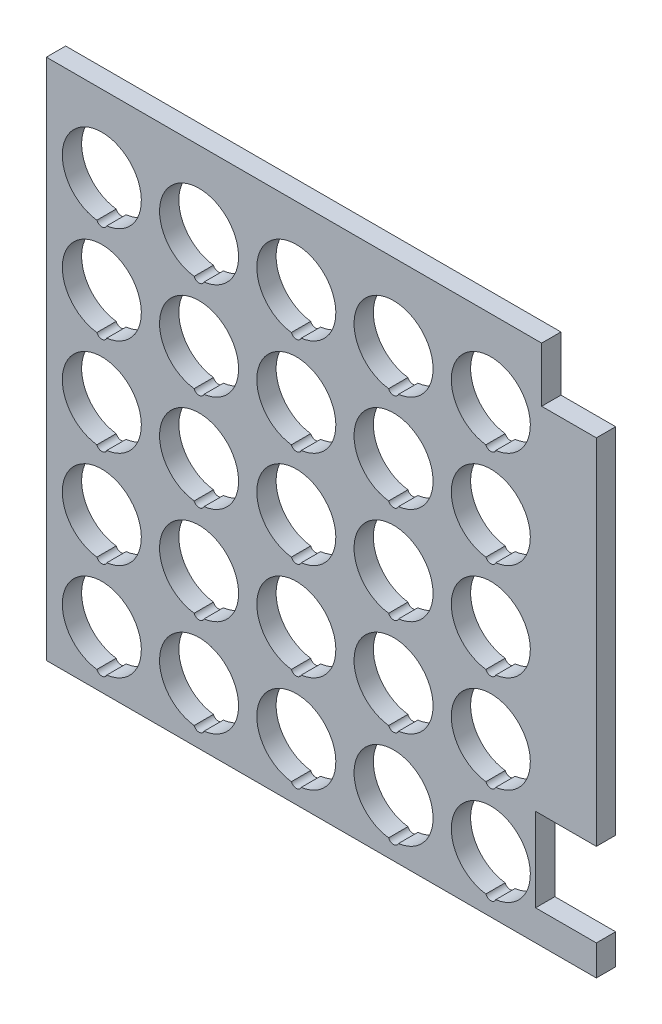
SolidWorks part; units mm, degrees
ref_plane "Front Plane" through (0, 0, 0) normal (0, 0, 1) x (1, 0, 0)
ref_plane "Top Plane" through (0, 0, 0) normal (0, 1, 0) x (1, 0, 0)
ref_plane "Right Plane" through (0, 0, 0) normal (1, 0, 0) x (0, 0, -1)
sketch "Sketch2" plane through (0, 0, 0) normal (0, 0, 1) x (1, 0, 0)
  line L1 (0, 0) -> (180.975, 0)
  line L2 (0, 0) -> (0, 161.925)
  line L3 (0, 161.925) -> (180.975, 161.925)
  line L4 (180.975, 0) -> (180.975, 161.925)
  dimension "D1" = 180.975
  dimension "D2" = 161.925
extrude "Boss-Extrude1" add sketch "Sketch2" along normal blind 6.35
sketch "Sketch6" plane through (0, 0, 6.35) normal (0, 0, 1) x (1, 0, 0)
  line L1 (0, 0) -> (180.975, 0)
  line L2 (0, 0) -> (0, -10)
  line L3 (0, -10) -> (180.975, -10)
  line L4 (180.975, 0) -> (180.975, -10)
  dimension "D1" = 10
extrude "Boss-Extrude2" add sketch "Sketch6" against normal up to surface (6.35 mm away) up to face at (90.4875, 80.9625, 0)
sketch "Sketch3" plane through (0, 0, 6.35) normal (0, 0, 1) x (1, 0, 0)
  line L2 (0, 161.925) -> (0, -10) construction
  line L3 (180.975, 161.925) -> (0, 161.925) construction
  circle A0 centre (18.25, 8.675) radius 13
  circle A1 centre (50.25, 8.675) radius 13
  circle A2 centre (82.25, 8.675) radius 13
  circle A3 centre (114.25, 8.675) radius 13
  circle A4 centre (146.25, 8.675) radius 13
  circle A5 centre (50.25, 40.675) radius 13
  circle A6 centre (82.25, 40.675) radius 13
  circle A7 centre (114.25, 40.675) radius 13
  circle A8 centre (146.25, 40.675) radius 13
  circle A9 centre (50.25, 72.675) radius 13
  circle A10 centre (82.25, 72.675) radius 13
  circle A11 centre (114.25, 72.675) radius 13
  circle A12 centre (146.25, 72.675) radius 13
  circle A13 centre (50.25, 104.675) radius 13
  circle A14 centre (82.25, 104.675) radius 13
  circle A15 centre (114.25, 104.675) radius 13
  circle A16 centre (146.25, 104.675) radius 13
  circle A17 centre (50.25, 136.675) radius 13
  circle A18 centre (82.25, 136.675) radius 13
  circle A19 centre (114.25, 136.675) radius 13
  circle A20 centre (146.25, 136.675) radius 13
  circle A21 centre (18.25, 40.675) radius 13
  circle A22 centre (18.25, 72.675) radius 13
  circle A23 centre (18.25, 104.675) radius 13
  circle A24 centre (18.25, 136.675) radius 13
  dimension "D2" = 25.25
  dimension "D3" = 26
  dimension "D1" = 18.25
  dimension "D4" = 5
  dimension "D5" = 5
extrude "Cut-Extrude1" cut sketch "Sketch3" against normal through all
sketch "Sketch4" plane through (0, 0, 6.35) normal (0, 0, 1) x (1, 0, 0)
  line L0 (18.25, 21.675) -> (18.25, -4.325) construction
  circle A0 centre (18.25, 8.675) radius 13 construction
  circle A1 centre (18.25, -3.575) radius 1.75
  circle A2 centre (50.25, -3.575) radius 1.75
  circle A3 centre (82.25, -3.575) radius 1.75
  circle A4 centre (114.25, -3.575) radius 1.75
  circle A5 centre (146.25, -3.575) radius 1.75
  circle A6 centre (50.25, 28.425) radius 1.75
  circle A7 centre (82.25, 28.425) radius 1.75
  circle A8 centre (114.25, 28.425) radius 1.75
  circle A9 centre (146.25, 28.425) radius 1.75
  circle A10 centre (50.25, 60.425) radius 1.75
  circle A11 centre (82.25, 60.425) radius 1.75
  circle A12 centre (114.25, 60.425) radius 1.75
  circle A13 centre (146.25, 60.425) radius 1.75
  circle A14 centre (50.25, 92.425) radius 1.75
  circle A15 centre (82.25, 92.425) radius 1.75
  circle A16 centre (114.25, 92.425) radius 1.75
  circle A17 centre (146.25, 92.425) radius 1.75
  circle A18 centre (50.25, 124.425) radius 1.75
  circle A19 centre (82.25, 124.425) radius 1.75
  circle A20 centre (114.25, 124.425) radius 1.75
  circle A21 centre (146.25, 124.425) radius 1.75
  circle A22 centre (18.25, 28.425) radius 1.75
  circle A23 centre (18.25, 60.425) radius 1.75
  circle A24 centre (18.25, 92.425) radius 1.75
  circle A25 centre (18.25, 124.425) radius 1.75
  dimension "D2" = 3.5
  dimension "D1" = 0.75
  dimension "D3" = 5
  dimension "D4" = 5
extrude "Cut-Extrude9" cut sketch "Sketch4" against normal through all
sketch "Sketch5" plane through (0, 0, 6.35) normal (0, 0, 1) x (1, 0, 0)
  line L0 (13, 140.675) -> (15.5, 140.675) construction
  circle A0 centre (13, 140.675) radius 1
  circle A1 centre (15.5, 140.675) radius 1
  point P4 (18.25, 136.675)
  point P5 (14.25, 140.675)
  dimension "D1" = 2
  dimension "D2" = 2
  dimension "D3" = 2.5
  dimension "D4" = 4
  dimension "D5" = 4
sketch "Sketch7" plane through (0, 0, 6.35) normal (0, 0, 1) x (1, 0, 0)
  line L0 (180.975, -10) -> (180.975, 161.925) construction
  line L1 (180.975, 0) -> (160.975, 0)
  line L2 (180.975, 0) -> (180.975, 27.5)
  line L3 (180.975, 27.5) -> (160.975, 27.5)
  line L4 (160.975, 0) -> (160.975, 27.5)
  line L5 (0, -10) -> (180.975, -10) construction
  line L6 (180.975, 161.925) -> (162.975, 161.925)
  line L7 (180.975, 161.925) -> (180.975, 143.925)
  line L8 (180.975, 143.925) -> (162.975, 143.925)
  line L9 (162.975, 161.925) -> (162.975, 143.925)
  dimension "D1" = 18
  dimension "D2" = 18
  dimension "D3" = 20
  dimension "D4" = 27.5
  dimension "D5" = 10
extrude "Cut-Extrude10" cut sketch "Sketch7" against normal through all
